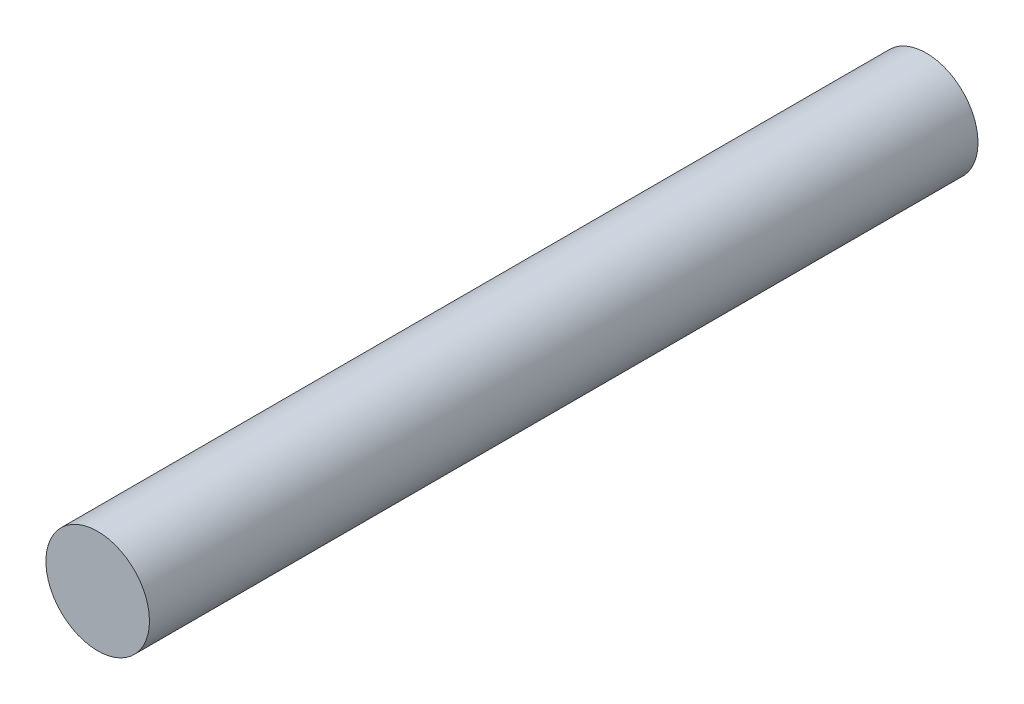
SolidWorks part; units mm, degrees
ref_plane "Front Plane" through (0, 0, 0) normal (0, 0, 1) x (1, 0, 0)
ref_plane "Top Plane" through (0, 0, 0) normal (0, 1, 0) x (1, 0, 0)
ref_plane "Right Plane" through (0, 0, 0) normal (1, 0, 0) x (0, 0, -1)
sketch "Sketch1" plane through (0, 0, 0) normal (0, 0, 1) x (1, 0, 0)
  circle A0 centre (0, 0) radius 6.35
  dimension "D1" = 12.7
extrude "Extrude1" add sketch "Sketch1" against normal mid plane 101.6
